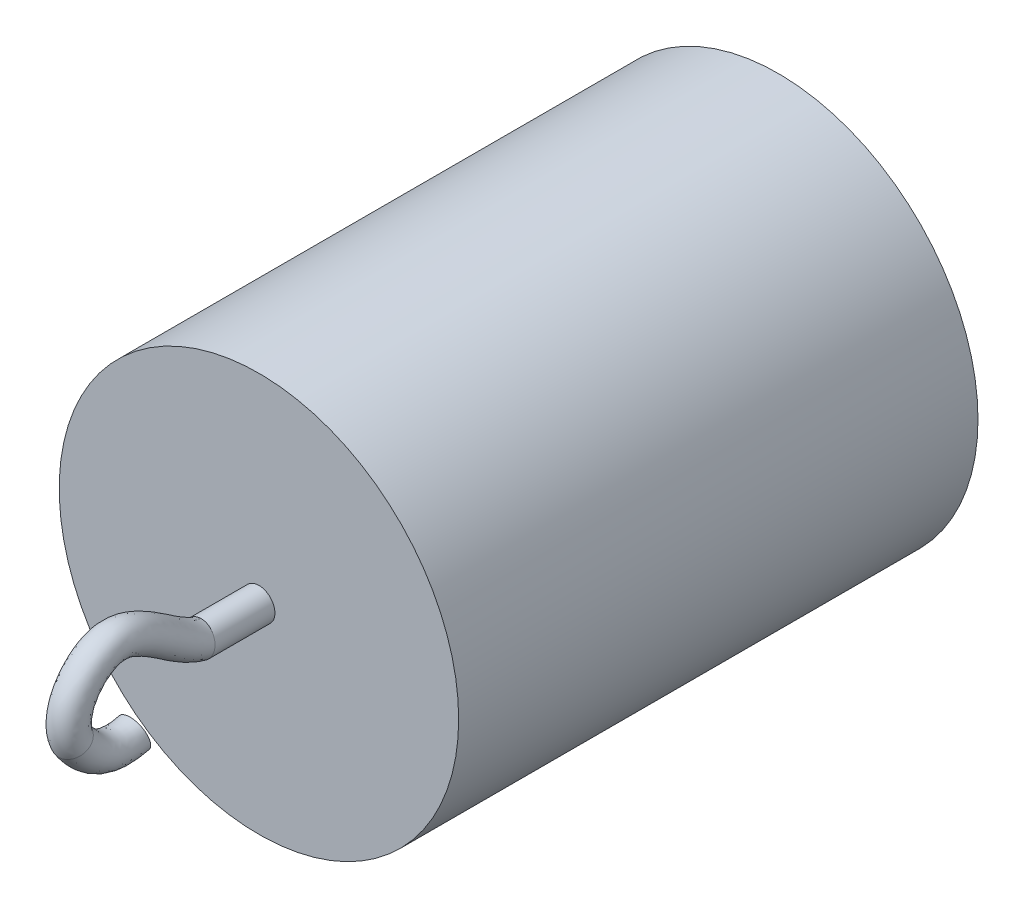
SolidWorks part; units mm, degrees
ref_plane "Front" through (0, 0, 0) normal (0, 0, 1) x (1, 0, 0)
ref_plane "Top" through (0, 0, 0) normal (0, 1, 0) x (1, 0, 0)
ref_plane "Right" through (0, 0, 0) normal (1, 0, 0) x (0, 0, -1)
sketch "草图1" plane through (0, 0, 0) normal (0, 0, 1) x (1, 0, 0)
  circle A0 centre (0, 0) radius 25
extrude "凸台-拉伸1" add sketch "草图1" along normal blind 65
sketch "草图2" plane through (0, 0, 0) normal (1, 0, 0) x (0, 0, -1)
  line L0 (0, 0) -> (-65, 0) construction
  line L1 (-65, 25) -> (-65, -25) construction
  line L2 (-65, 0) -> (-95.5738, 0) construction
  line L3 (-72.5169, 0) -> (-65, 0)
  spline S0 degree 3 poles (-88.3685, -3.0484) (-89.9565, -0.0339) (-83.5323, 9.8764) (-76.1356, 1.0195) (-72.5169, 0) knots 0 0 0 0 0.436986 1 1 1 1
  spline S1 degree 2 poles (-88.3685, -3.0484) (-85.3937, -7.4223) (-80.609, -6.1522) knots 0 0 0 1 1 1
sketch "草图3" plane through (0, 0, 65) normal (0, 0, 1) x (1, 0, 0)
  circle A0 centre (0, 0) radius 2
  dimension "D1" = 4
surface "曲面-扫描1"
